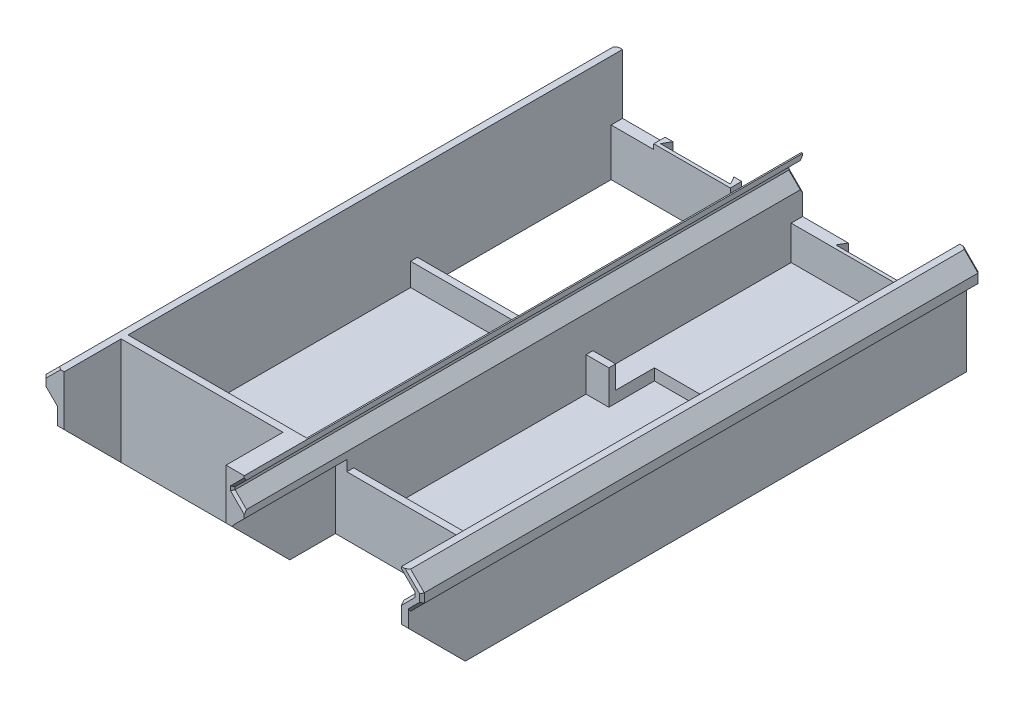
SolidWorks part; units mm, degrees
ref_plane "前视基准面" through (0, 0, 0) normal (0, 0, 1) x (1, 0, 0)
ref_plane "上视基准面" through (0, 0, 0) normal (0, 1, 0) x (1, 0, 0)
ref_plane "右视基准面" through (0, 0, 0) normal (1, 0, 0) x (0, 0, -1)
other "Configuration Table"
sketch "草图1" plane through (0, 0, 0) normal (0, 0, 1) x (1, 0, 0)
  line L0 (77, 0) -> (-77, 0)
  line L1 (-77, 0) -> (-77, 31)
  line L2 (-77, 31) -> (-83, 37)
  line L3 (-83, 37) -> (-83, 41)
  line L4 (-83, 41) -> (-77, 47)
  line L5 (-77, 47) -> (77, 47)
  line L6 (0, 47) -> (0, 0) construction
  line L7 (83, 41) -> (77, 47)
  line L8 (83, 37) -> (83, 41)
  line L9 (77, 31) -> (83, 37)
  line L10 (77, 0) -> (77, 31)
  point P10 (0, 23.5)
  point P11 (-83, 39)
  dimension "D1" = 77
  dimension "D2" = 47
  dimension "D3" = 45
  dimension "D4" = 45
  dimension "D5" = 6
  dimension "D6" = 16
extrude "凸台-拉伸1" add sketch "草图1" against normal blind 200
sketch "草图3" plane through (0, 47, 0) normal (0, 1, 0) x (1, 0, 0)
  line L8 (-74, 3) -> (74, 3)
  line L9 (74, 3) -> (74, 197)
  line L10 (74, 197) -> (-74, 197)
  line L11 (-74, 197) -> (-74, 3)
  line L12 (-74, 3) -> (74, 3)
  line L13 (74, 3) -> (74, 197)
  line L14 (74, 197) -> (-74, 197)
  line L15 (-74, 197) -> (-74, 3)
  dimension "D1" = 3
extrude "切除-拉伸1" cut sketch "草图3" against normal offset from surface (44 mm away) 3 up to face at (0, 0, -100)
sketch "草图4" plane through (0, 3, 0) normal (0, 1, 0) x (1, 0, 0)
  line L0 (0, 3) -> (0, 197)
  line L1 (-74, 3) -> (74, 3) construction
  line L2 (74, 197) -> (-74, 197) construction
extrude "拉伸-薄壁1" add sketch "草图4" along normal up to surface (44 mm away) thin
sketch "草图5" plane through (0, 0, -200) normal (0, 0, -1) x (-1, 0, 0)
  line L0 (-74, 47) -> (-74, 44.7674)
  line L1 (-77, 47) -> (77, 47) construction
  line L2 (-74, 44.7674) -> (-79, 39.7674)
  line L3 (-79, 39.7674) -> (-79, 38.6569)
  line L4 (-79, 38.6569) -> (-74, 33.6569)
  line L5 (-74, 33.6569) -> (-74, 26)
  line L6 (-74, 26) -> (-5, 26)
  line L7 (-5, 26) -> (-5, 33.6569)
  line L8 (-5, 33.6569) -> (0, 38.6569)
  line L9 (0, 38.6569) -> (0, 39.7674)
  line L10 (0, 39.7674) -> (-5, 44.7674)
  line L11 (-5, 44.7674) -> (-5, 47)
  line L12 (-5, 47) -> (-74, 47)
  line L13 (-73, 44.3532) -> (-78, 39.3532) construction
  line L14 (-74, 3) -> (-74, 47) construction
  line L15 (-78, 37.6569) -> (-73, 32.6569) construction
  line L16 (-78, 39.3532) -> (-78, 37.6569) construction
  line L17 (-73, 28) -> (-6, 28) construction
  line L18 (-6, 32.6569) -> (-1, 37.6569) construction
  line L19 (-1, 37.6569) -> (-1, 39.3532) construction
  line L20 (-1, 39.3532) -> (-6, 44.3532) construction
  line L21 (-5, 47) -> (-5, 3) construction
  dimension "D1" = 1
  dimension "D2" = 1
  dimension "D3" = 2
  dimension "D4" = 1
  dimension "D5" = 1
extrude "切除-拉伸2" cut sketch "草图5" against normal through all
sketch "草图9" plane through (0, 0, -3) normal (0, 0, -1) x (-1, 0, 0)
  line L0 (-4.4042, 47) -> (3, 39.5958)
  line L1 (-5, 47) -> (77, 47) construction
  line L2 (3, 39.5958) -> (3, 47) construction
  line L3 (3, 47) -> (-4.4042, 47)
  line L4 (0, 39.7674) -> (-5, 44.7674) construction
  line L5 (3, 47) -> (3, 3) construction
  line L6 (3, 39.5958) -> (74, 39.5958)
  line L7 (74, 3) -> (74, 47) construction
  line L8 (74, 39.5958) -> (74, 47)
  line L9 (74, 47) -> (3, 47)
  dimension "D1" = 2
extrude "切除-拉伸5" cut sketch "草图9" along normal through all
other "移动面1" face at (39.5, 14.5, -197) face at (-38.5, 21.2979, -197) parameters "D1"=2
sketch "草图11" plane through (0, 0, 0) normal (0, -1, 0) x (1, 0, 0)
  line L0 (51.8834, -200) -> (53.9041, -196.5)
  line L1 (72.5, -200) -> (-72.5, -200) construction
  line L2 (53.9041, -196.5) -> (23.0959, -196.5)
  line L3 (23.0959, -196.5) -> (25.1166, -200)
  line L4 (25.1166, -200) -> (51.8834, -200)
  line L5 (51.7679, -200) -> (53.5, -197) construction
  line L6 (23.5, -197) -> (25.2321, -200) construction
  line L7 (52.3453, -197) -> (24.6547, -197) construction
  line L8 (0, -200) -> (0, -208.8096) construction
  line L9 (-53.9041, -196.5) -> (-23.0959, -196.5)
  line L10 (-51.8834, -200) -> (-53.9041, -196.5)
  line L11 (-25.1166, -200) -> (-51.8834, -200)
  line L12 (-23.0959, -196.5) -> (-25.1166, -200)
  dimension "D1" = 0.1
  dimension "D2" = 0.1
  dimension "D3" = 0.5
extrude "切除-拉伸6" cut sketch "草图11" against normal through all
sketch "草图12" plane through (0, 39.5958, 0) normal (0, 1, 0) x (1, 0, 0)
  line L8 (-53.9041, 196.5) -> (-51.8834, 200)
  line L9 (-51.8834, 200) -> (-74, 200)
  line L10 (-74, 200) -> (-74, 195)
  line L11 (-74, 195) -> (-3, 195)
  line L12 (-3, 195) -> (-3, 200)
  line L13 (-3, 200) -> (-25.1166, 200)
  line L14 (-25.1166, 200) -> (-23.0959, 196.5)
  line L15 (-23.0959, 196.5) -> (-53.9041, 196.5)
  line L16 (-53.9041, 196.5) -> (-51.8834, 200)
  line L17 (-51.8834, 200) -> (-74, 200)
  line L18 (-74, 200) -> (-74, 195)
  line L19 (-74, 195) -> (-3, 195)
  line L20 (-3, 195) -> (-3, 200)
  line L21 (-3, 200) -> (-25.1166, 200)
  line L22 (-25.1166, 200) -> (-23.0959, 196.5)
  line L23 (-23.0959, 196.5) -> (-53.9041, 196.5)
  line L24 (53.9041, 196.5) -> (23.0959, 196.5)
  line L25 (23.0959, 196.5) -> (25.1166, 200)
  line L26 (25.1166, 200) -> (5, 200)
  line L27 (5, 200) -> (5, 195)
  line L28 (5, 195) -> (74, 195)
  line L29 (74, 195) -> (74, 200)
  line L30 (74, 200) -> (51.8834, 200)
  line L31 (51.8834, 200) -> (53.9041, 196.5)
  line L32 (53.9041, 196.5) -> (23.0959, 196.5)
  line L33 (23.0959, 196.5) -> (25.1166, 200)
  line L34 (25.1166, 200) -> (5, 200)
  line L35 (5, 200) -> (5, 195)
  line L36 (5, 195) -> (74, 195)
  line L37 (74, 195) -> (74, 200)
  line L38 (74, 200) -> (51.8834, 200)
  line L39 (51.8834, 200) -> (53.9041, 196.5)
  dimension "D1" = 0
  dimension "D2" = 0
extrude "切除-拉伸7" cut sketch "草图12" against normal up to vertex (16.5958 mm away)
other "移动面2" face at (21.5455, 35.0771, 0) parameters "D1"=45
other "移动面3" face at (-29.9192, 27.9192, -3) parameters "D1"=20
sketch "草图13" plane through (0, 0, 45) normal (0, 0, 1) x (1, 0, 0)
  line L0 (-77, 0) -> (77, 0) construction
  line L1 (-74, 47) -> (-3, 47)
  line L2 (-74, 47) -> (-74, 0)
  line L3 (-74, 0) -> (-3, 0)
  line L4 (-3, 47) -> (-3, 0)
  line L5 (-3, 39.5958) -> (-3, 3) construction
extrude "切除-拉伸8" cut sketch "草图13" against normal offset from surface (25 mm away) 3 up to face at (-29.9192, 27.9192, 17)
sketch "草图14" plane through (0, 0, 45) normal (0, 0, 1) x (1, 0, 0)
  line L0 (-3, 0) -> (77, 0) construction
  line L1 (74, 26) -> (5, 26)
  line L2 (74, 26) -> (74, 0)
  line L3 (74, 0) -> (5, 0)
  line L4 (5, 26) -> (5, 0)
  line L5 (5, 26) -> (5, 33.6569) construction
extrude "切除-拉伸9" cut sketch "草图14" against normal offset from surface (45 mm away) 3 up to face at (39.5, 14.5, -3)
sketch "草图15" plane through (0, 0, 45) normal (0, 0, 1) x (1, 0, 0)
  line L0 (5, 0) -> (0, 0)
  line L1 (-3, 0) -> (5, 0) construction
  line L2 (0, 0) -> (0, 25.6569)
  line L3 (0, 25.6569) -> (5, 30.6569)
  line L4 (5, 0) -> (5, 33.6569) construction
  line L5 (5, 30.6569) -> (5, 0)
  line L6 (-3, 0) -> (-3, 47) construction
  point P11 (5, 32.2564)
  dimension "D1" = 3
  dimension "D2" = 45
  dimension "D3" = 3
extrude "切除-拉伸10" cut sketch "草图15" against normal up to surface (45 mm away) up to face at (39.5, 13, 0)
chamfer "倒角1" distance 25 angle 45 3 edges at (75.5, 0, 45) (-1.5, 0, 45) (-75.5, 0, 45)
sketch "草图16" plane through (0, 3, 0) normal (0, 1, 0) x (1, 0, 0)
  line L0 (-74, 200) -> (-74, -17) construction
  line L1 (-3, 195) -> (-74, 195)
  line L2 (-3, 195) -> (-3, 110)
  line L3 (-3, 110) -> (-74, 110)
  line L4 (-74, 195) -> (-74, 110)
  dimension "D1" = 85
extrude "切除-拉伸11" cut sketch "草图16" against normal up to next
sketch "草图17" plane through (0, 3, 0) normal (0, 1, 0) x (1, 0, 0)
  line L0 (-3, -17) -> (-3, 200) construction
  line L1 (-74, 110) -> (-3, 110)
  line L2 (-74, 110) -> (-74, 107)
  line L3 (-74, 107) -> (-3, 107)
  line L4 (-3, 110) -> (-3, 107)
  dimension "D1" = 3
extrude "凸台-拉伸2" add sketch "草图17" along normal blind 10
sketch "草图18" plane through (0, 23, 0) normal (0, 1, 0) x (1, 0, 0)
  line L0 (-74, 195) -> (-3, 195) construction
  line L1 (-3, 200) -> (-21.7, 200)
  line L2 (-3, 200) -> (-3, 195)
  line L3 (-3, 195) -> (-21.7, 195)
  line L4 (-21.7, 200) -> (-21.7, 195)
  line L5 (-55.8, 194.8) -> (-55.8, 199.5) construction
  line L6 (-74, 200) -> (-55.3, 200)
  line L7 (-74, 200) -> (-74, 195)
  line L8 (-74, 195) -> (-55.3, 195)
  line L9 (-55.3, 200) -> (-55.3, 195)
  line L10 (-21.2, 199.5) -> (-21.2, 194.8) construction
  dimension "D1" = 0.5
  dimension "D2" = 0.5
extrude "切除-拉伸12" cut sketch "草图18" against normal blind 2.2
sketch "草图19" plane through (0, 3, 0) normal (0, 1, 0) x (1, 0, 0)
  line L0 (5, -45) -> (5, 200) construction
  line L1 (74, 195) -> (5, 195)
  line L2 (74, 195) -> (74, 105)
  line L3 (74, 105) -> (5, 105)
  line L4 (5, 195) -> (5, 105)
  dimension "D1" = 90
extrude "凸台-拉伸3" add sketch "草图19" along normal blind 15
sketch "草图20" plane through (0, 18, 0) normal (0, 1, 0) x (1, 0, 0)
  line L1 (5, 195) -> (61, 195)
  line L2 (5, 195) -> (5, 108)
  line L3 (5, 108) -> (61, 108)
  line L4 (61, 195) -> (61, 108)
  dimension "D1" = 87
  dimension "D2" = 56
extrude "切除-拉伸13" cut sketch "草图20" against normal blind 10
sketch "草图21" plane through (0, 18, 0) normal (0, 1, 0) x (1, 0, 0)
  line L0 (5, 108) -> (61, 108) construction
  line L1 (15, 125) -> (51, 125)
  line L2 (15, 125) -> (15, 91)
  line L3 (15, 91) -> (51, 91)
  line L4 (51, 125) -> (51, 91)
  line L5 (33, 91) -> (33, 125) construction
  line L6 (15, 108) -> (51, 108) construction
  line L7 (5, 105) -> (74, 105) construction
  line L8 (61, 108) -> (61, 195) construction
  point P0 (33, 108)
  dimension "D1" = 20
  dimension "D2" = 10
extrude "切除-拉伸14" cut sketch "草图21" against normal up to surface (15 mm away) up to face at (39.5, 3, -54)
sketch "草图22" plane through (0, 18, 0) normal (0, 1, 0) x (1, 0, 0)
  line L0 (65, 190) -> (65, 173)
  line L1 (65, 167) -> (65, 150)
  line L2 (65, 144) -> (65, 109)
  line L3 (61, 108) -> (61, 195) construction
  line L5 (5, 195) -> (74, 195) construction
  point P8 (65, 190.843)
  dimension "D1" = 4
  dimension "D2" = 5
  dimension "D3" = 17
  dimension "D4" = 6
  dimension "D5" = 6
  dimension "D6" = 35
extrude "切除-拉伸-薄壁1" cut sketch "草图22" against normal blind 7 thin thin type one direction reverse wall 2
other "移动面4" face at (66, 11, -126.5) parameters "D1"=3
chamfer "倒角2" distance 1 angle 45 23 edges at (76.5, 36.1569, -200) (76.5, 42.2674, -200) (80, 44, -200) (83, 39, -200) (80, 34, -200) (-80, 44, 45) (-80, 34, 45) (-83, 39, 45) (-80, 44, -200) (-83, 39, -200) (-80, 34, -200) (2.5, 42.2674, -200) (0, 39.2121, -200) (2.5, 36.1569, -200) (2.5, 42.2674, 45) (0, 39.2121, 45) (2.5, 36.1569, 45) (76.5, 42.2674, 45) (79, 39.2121, 45) (76.5, 36.1569, 45) (80, 44, 45) (83, 39, 45) (80, 34, 45)
